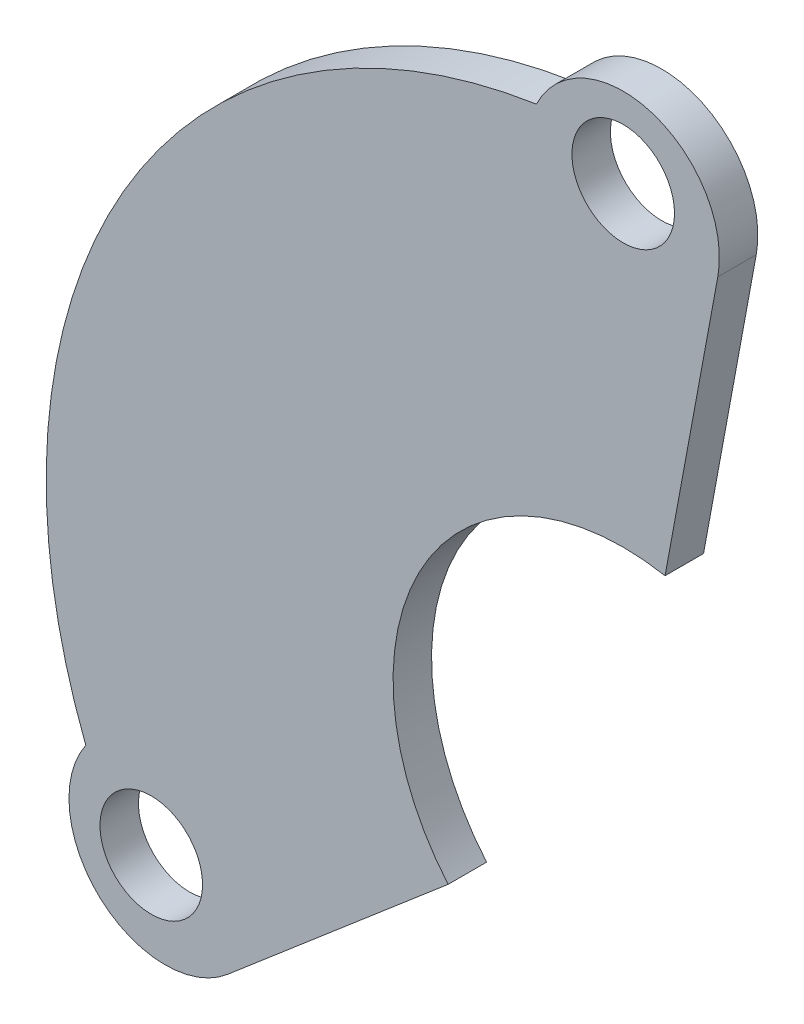
SolidWorks part; units mm, degrees
ref_plane "前视基准面" through (0, 0, 0) normal (0, 0, 1) x (1, 0, 0)
ref_plane "上视基准面" through (0, 0, 0) normal (0, 1, 0) x (1, 0, 0)
ref_plane "右视基准面" through (0, 0, 0) normal (1, 0, 0) x (0, 0, -1)
sketch "草图1" plane through (0, 0, 0) normal (0, 0, 1) x (1, 0, 0)
  circle A0 centre (0, 0) radius 7.18
  arc A1 (-14.0584, -11.2411) -> (14.0584, -11.2411) centre (0, 0) ccw
  circle A2 centre (0, 0) radius 16.5 construction
  arc A3 (2.7059, 17.7955) -> (-2.7059, 17.7955) centre (0, 16.5) ccw
  arc A4 (14.0584, -11.2411) -> (16.7643, -6.5544) centre (14.2894, -8.25) ccw
  arc A5 (-16.7643, -6.5544) -> (-14.0584, -11.2411) centre (-14.2894, -8.25) ccw
  arc A6 (16.7643, -6.5544) -> (2.7059, 17.7955) centre (0, 0) ccw
  arc A7 (-2.7059, 17.7955) -> (-16.7643, -6.5544) centre (0, 0) ccw
  point P14 (0, 0)
  dimension "D1" = 3
extrude "凸台-拉伸1" add sketch "草图1" along normal blind 1.2
sketch "草图2" plane through (0, 0, 1.2) normal (0, 0, 1) x (1, 0, 0)
  circle A0 centre (0, 0) radius 17 construction
  circle A1 centre (0, 17) radius 1.6
  circle A2 centre (14.7224, -8.5) radius 1.6
  circle A3 centre (-14.7224, -8.5) radius 1.6
  point P12 (0, 0)
extrude "切除-拉伸1" cut sketch "草图2" against normal blind 10
ref_plane "基准面1" through (0, 0, 11.2) normal (0, 0, 1) x (1, 0, 0)
sketch "草图4" plane through (0, 0, 11.2) normal (0, 0, 1) x (1, 0, 0)
  line L0 (0, 0) -> (2.95, 15.9545)
  line L1 (0, 0) -> (-12.9904, 7.5) construction
  line L2 (0, 0) -> (-12.342, -10.532)
  line L3 (-16.7643, -6.5544) -> (-25.4209, -11.8631)
  line L4 (-25.4209, -11.8631) -> (-5.7098, -19.189)
  line L5 (-5.7098, -19.189) -> (30.2721, -16.8415)
  line L6 (30.2721, -16.8415) -> (9.4508, 25.3671)
  line L7 (9.4508, 25.3671) -> (-0.61, 23.6331)
  line L8 (-0.61, 23.6331) -> (-2.7059, 17.7955)
  arc A0 (-2.7059, 17.7955) -> (2.95, 15.9545) centre (0, 16.5) cw
  arc A1 (-16.7643, -6.5544) -> (-12.342, -10.532) centre (-14.2894, -8.25) ccw
extrude "切除-拉伸4" cut sketch "草图4" against normal up to surface (11.2 mm away) contours L6 L7 L8 A0 L0 L2 A1 L3 L4 L5 up to face at (1.6, 17, 0)
